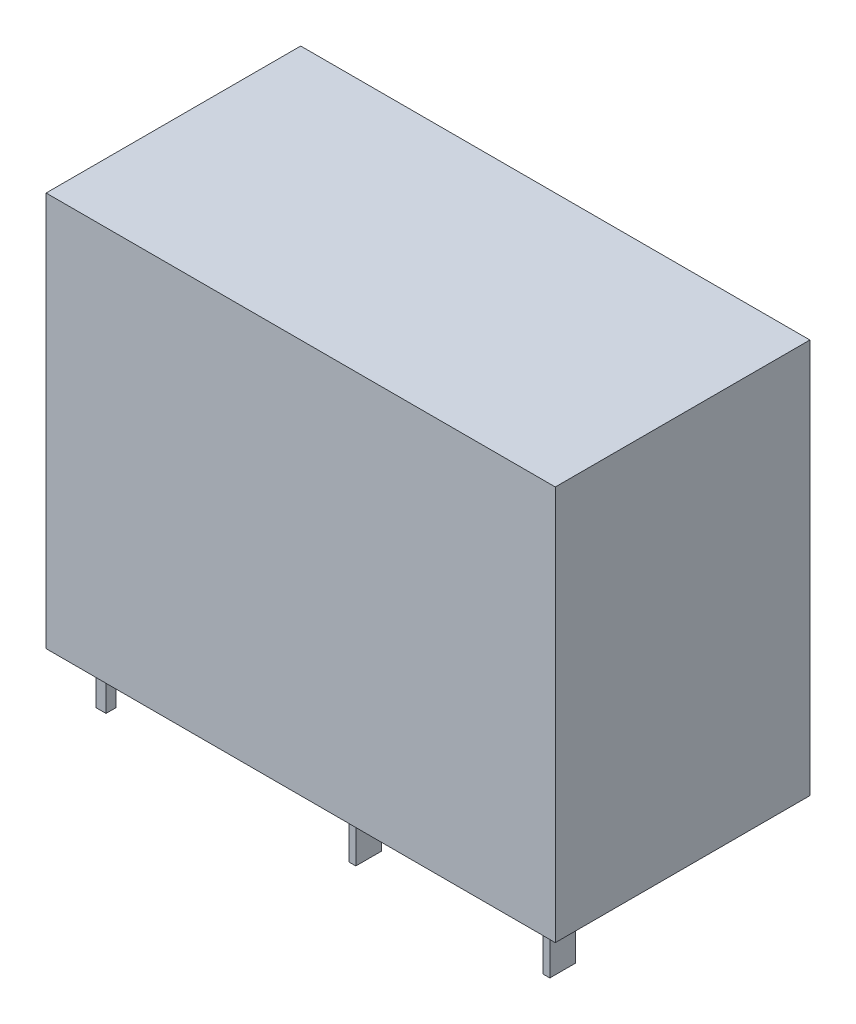
SolidWorks part; units mm, degrees
ref_plane "Спереди" through (0, 0, 0) normal (0, 0, 1) x (1, 0, 0)
ref_plane "Сверху" through (0, 0, 0) normal (0, 1, 0) x (1, 0, 0)
ref_plane "Справа" through (0, 0, 0) normal (1, 0, 0) x (0, 0, -1)
sketch "Эскиз1" plane through (0, 0, 0) normal (0, 1, 0) x (1, 0, 0)
  line L1 (-10, -5) -> (10, -5)
  line L2 (-10, -5) -> (-10, 5)
  line L3 (-10, 5) -> (10, 5)
  line L4 (10, -5) -> (10, 5)
  line L5 (-10, -5) -> (10, 5) construction
  line L6 (-10, 5) -> (10, -5) construction
  point P0 (0, 0)
  dimension "D1" = 20
  dimension "D2" = 10
extrude "Бобышка-Вытянуть1" add sketch "Эскиз1" along normal blind 15.5
sketch "Эскиз2" plane through (0, 0, 0) normal (0, 1, 0) x (1, 0, 0)
  line L0 (0, 7.046) -> (0, -7.8067) construction
  line L5 (-8.82, 10.2512) -> (-8.82, -8.0356) construction
  line L6 (10, -5) -> (-10, -5) construction
  line L7 (10, -5) -> (10, 5) construction
  line L8 (10, 5) -> (-10, 5) construction
  line L9 (-10, -5) -> (-10, 5) construction
  line L10 (10, -5) -> (-10, 5) construction
  line L11 (10, 5) -> (-10, -5) construction
  line L12 (1.34, 10.8236) -> (1.34, -8.4362) construction
  line L13 (8.96, 10.0795) -> (8.96, -8.4362) construction
  line L14 (-14.1816, 3.81) -> (14.2645, 3.81) construction
  line L15 (-15.3836, -3.81) -> (13.2915, -3.81) construction
  line L17 (-9.02, 3.61) -> (-8.62, 3.61)
  line L18 (-9.02, 3.61) -> (-9.02, 4.01)
  line L19 (-9.02, 4.01) -> (-8.62, 4.01)
  line L20 (-8.62, 3.61) -> (-8.62, 4.01)
  line L21 (-9.02, 3.61) -> (-8.62, 4.01) construction
  line L22 (-9.02, 4.01) -> (-8.62, 3.61) construction
  line L23 (-9.02, -4.0281) -> (-8.62, -4.0281)
  line L24 (-9.02, -4.0281) -> (-9.02, -3.6281)
  line L25 (-9.02, -3.6281) -> (-8.62, -3.6281)
  line L26 (-8.62, -4.0281) -> (-8.62, -3.6281)
  line L27 (-9.02, -4.0281) -> (-8.62, -3.6281) construction
  line L28 (-9.02, -3.6281) -> (-8.62, -4.0281) construction
  line L29 (1.205, -4.31) -> (1.475, -4.31)
  line L30 (1.205, -4.31) -> (1.205, -3.31)
  line L31 (1.205, -3.31) -> (1.475, -3.31)
  line L32 (1.475, -4.31) -> (1.475, -3.31)
  line L33 (1.205, -4.31) -> (1.475, -3.31) construction
  line L34 (1.205, -3.31) -> (1.475, -4.31) construction
  line L35 (9.095, -4.31) -> (8.825, -4.31)
  line L36 (9.095, -4.31) -> (9.095, -3.31)
  line L37 (9.095, -3.31) -> (8.825, -3.31)
  line L38 (8.825, -4.31) -> (8.825, -3.31)
  line L39 (9.095, -4.31) -> (8.825, -3.31) construction
  line L40 (9.095, -3.31) -> (8.825, -4.31) construction
  line L41 (6.285, 3.31) -> (6.555, 3.31)
  line L42 (6.285, 3.31) -> (6.285, 4.31)
  line L43 (6.285, 4.31) -> (6.555, 4.31)
  line L44 (6.555, 3.31) -> (6.555, 4.31)
  line L45 (6.285, 3.31) -> (6.555, 4.31) construction
  line L46 (6.285, 4.31) -> (6.555, 3.31) construction
  point P0 (0, 0)
  point P17 (-8.82, 3.81)
  point P23 (-8.82, -3.8281)
  point P28 (1.34, -3.81)
  point P33 (8.96, -3.81)
  point P38 (6.42, 3.81)
  dimension "D1" = 10
  dimension "D2" = 20
  dimension "D3" = 1.18
  dimension "D4" = 10.16
  dimension "D5" = 7.62
  dimension "D6" = 1.19
  dimension "D7" = 7.62
  dimension "D8" = 0.4
  dimension "D9" = 0.4
  dimension "D10" = 0.4
  dimension "D11" = 0.4
  dimension "D12" = 1
  dimension "D13" = 1
  dimension "D14" = 0.27
  dimension "D15" = 0.27
  dimension "D16" = 1
  dimension "D17" = 0.27
  dimension "D18" = 5.08
extrude "Бобышка-Вытянуть2" add sketch "Эскиз2" against normal blind 2 separate body
equation "\"D9@Эскиз2\"=\"D8@Эскиз2\""
equation "\"D10@Эскиз2\"=\"D8@Эскиз2\""
equation "\"D11@Эскиз2\"=\"D8@Эскиз2\""
equation "\"D13@Эскиз2\"=\"D12@Эскиз2\""
equation "\"D15@Эскиз2\"=\"D14@Эскиз2\""
equation "\"D16@Эскиз2\"=\"D12@Эскиз2\""
equation "\"D17@Эскиз2\"=\"D14@Эскиз2\""
